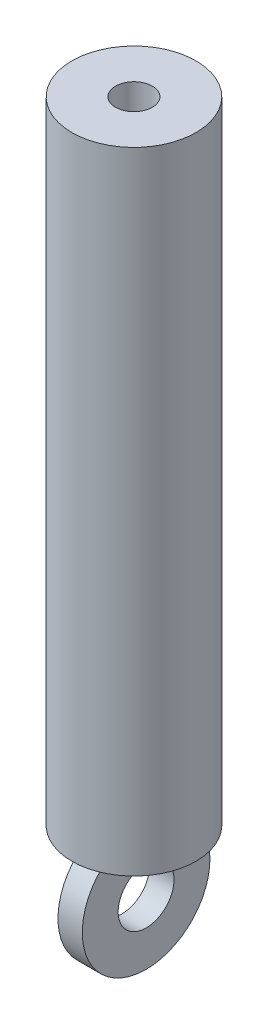
SolidWorks part; units mm, degrees
ref_plane "Front Plane" through (0, 0, 0) normal (0, 0, 1) x (1, 0, 0)
ref_plane "Top Plane" through (0, 0, 0) normal (0, 1, 0) x (1, 0, 0)
ref_plane "Right Plane" through (0, 0, 0) normal (1, 0, 0) x (0, 0, -1)
sketch "Sketch1" plane through (0, 0, 0) normal (0, 1, 0) x (1, 0, 0)
  circle A0 centre (0, 0) radius 4.5466
  circle A1 centre (0, 0) radius 1.3462
  dimension "D1" = 9.0932
  dimension "D2" = 2.6924
extrude "Extrude1" add sketch "Sketch1" along normal blind 35.56 and the other way blind 10.6413 from offset 1.27
sketch "Sketch4" plane through (0, 0, 0) normal (1, 0, 0) x (0, 0, -1)
  line L0 (4.5466, 36.83) -> (-4.5466, 36.83) construction
  line L2 (0, -13.3858) -> (0, 56.5912) construction
  circle A0 centre (0, -13.3858) radius 4.6736
  circle A1 centre (0, -13.3858) radius 2.0447
  dimension "D1" = 50.2158
  dimension "D2" = 9.3472
  dimension "D3" = 4.0894
extrude "Extrude2" add sketch "Sketch4" along normal mid plane 1.778 separate body
